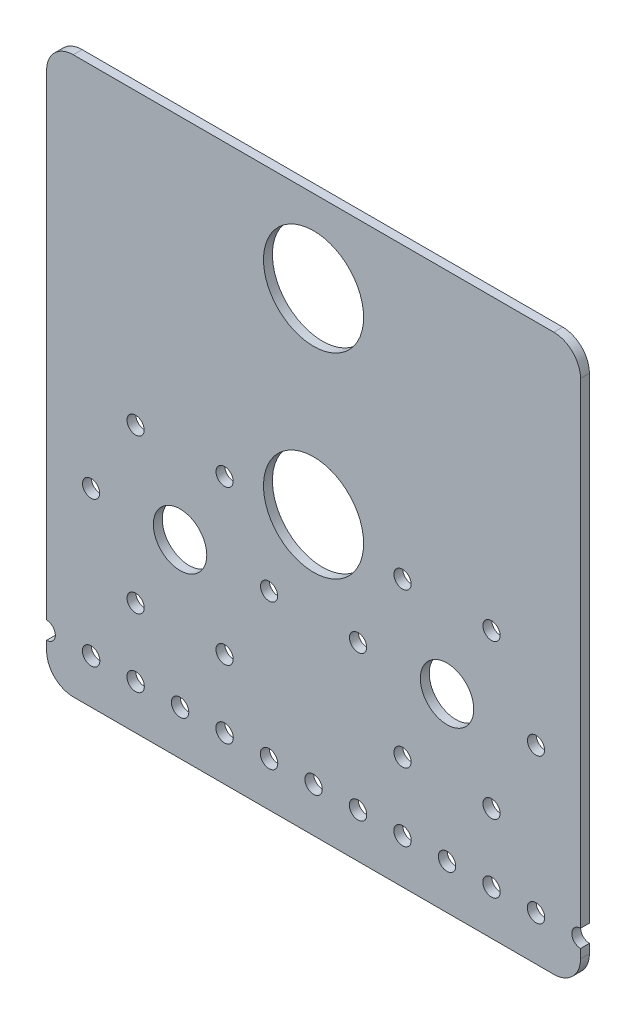
SolidWorks part; units mm, degrees
ref_plane "Front Plane" through (0, 0, 0) normal (0, 0, 1) x (1, 0, 0)
ref_plane "Top Plane" through (0, 0, 0) normal (0, 1, 0) x (1, 0, 0)
ref_plane "Right Plane" through (0, 0, 0) normal (1, 0, 0) x (0, 0, -1)
sketch "Sketch1" plane through (0, 0, 0) normal (0, 0, 1) x (1, 0, 0)
  line L0 (38.1, 28.7023) -> (25.4, 50.6994) construction
  line L1 (-38.1, 28.7023) -> (-50.8, 50.6994) construction
  line L2 (-95.25, -25.4) -> (-95.25, 0)
  line L3 (-95.25, 0) -> (-95.25, 107.95)
  line L6 (95.25, 107.95) -> (95.25, -25.4)
  line L7 (95.25, -25.4) -> (-95.25, -25.4)
  line L8 (-69.85, 133.35) -> (69.85, 133.35)
  line L10 (-95.25, 0) -> (95.25, 0) construction
  line L11 (-76.2, 133.35) -> (76.2, 133.35)
  line L12 (101.6, -12.7) -> (88.9, -12.7) construction
  line L13 (-95.25, 107.95) -> (-95.25, 133.35)
  line L14 (-95.25, 133.35) -> (-69.85, 133.35)
  line L15 (0, 53.975) -> (0, 133.35) construction
  line L16 (95.25, 107.95) -> (95.25, 133.35)
  line L17 (95.25, 133.35) -> (69.85, 133.35)
  line L18 (0, 0) -> (0, -25.4) construction
  line L19 (-76.2, 133.35) -> (-76.2, -25.4)
  line L20 (-76.2, -25.4) -> (76.2, -25.4)
  line L21 (76.2, 133.35) -> (76.2, -25.4)
  line L22 (0, 53.975) -> (0, 109.855)
  circle A0 centre (38.1, 28.7023) radius 7.62
  circle A1 centre (-38.1, 28.7023) radius 7.62
  circle A2 centre (0, 53.975) radius 38.1
  circle A3 centre (0, 53.975) radius 10.16
  circle A5 centre (-38.1, 28.7023) radius 25.4 construction
  circle A6 centre (38.1, 28.7023) radius 25.4 construction
  circle A7 centre (-50.8, 50.6994) radius 2.4511
  circle A8 centre (25.4, 50.6994) radius 2.4511
  circle A9 centre (50.8, 50.6994) radius 2.4511
  circle A10 centre (63.5, 28.7023) radius 2.4511
  circle A11 centre (50.8, 6.7053) radius 2.4511
  circle A12 centre (25.4, 6.7053) radius 2.4511
  circle A13 centre (12.7, 28.7023) radius 2.4511
  circle A14 centre (-25.4, 50.6994) radius 2.4511
  circle A15 centre (-12.7, 28.7023) radius 2.4511
  circle A16 centre (-25.4, 6.7053) radius 2.4511
  circle A17 centre (-50.8, 6.7053) radius 2.4511
  circle A18 centre (-63.5, 28.7023) radius 2.4511
  circle A19 centre (-38.1, 28.7023) radius 9.525
  circle A20 centre (38.1, 28.7023) radius 9.525
  circle A21 centre (0, 53.975) radius 14.2875
  circle A23 centre (101.6, -12.7) radius 2.4892
  circle A24 centre (88.9, -12.7) radius 2.4892
  circle A25 centre (76.2, -12.7) radius 2.4892
  circle A26 centre (63.5, -12.7) radius 2.4892
  circle A27 centre (50.8, -12.7) radius 2.4892
  circle A28 centre (38.1, -12.7) radius 2.4892
  circle A29 centre (25.4, -12.7) radius 2.4892
  circle A30 centre (12.7, -12.7) radius 2.4892
  circle A31 centre (0, -12.7) radius 2.4892
  circle A32 centre (-12.7, -12.7) radius 2.4892
  circle A33 centre (-25.4, -12.7) radius 2.4892
  circle A34 centre (-38.1, -12.7) radius 2.4892
  circle A35 centre (-50.8, -12.7) radius 2.4892
  circle A36 centre (-63.5, -12.7) radius 2.4892
  circle A37 centre (-76.2, -12.7) radius 2.4892
  circle A38 centre (-88.9, -12.7) radius 2.4892
  circle A39 centre (0, 109.855) radius 14.2875
  point P89 (0, 0)
  point P90 (0, 0)
  point P91 (102.1917, -12.7)
  point P92 (0, 0)
  point P93 (0, 0)
  point P95 (0, 0)
  point P96 (0, 0)
  dimension "D1" = 15.24
  dimension "D2" = 76.2
  dimension "D5" = 20.32
  dimension "D6" = 6.35
  dimension "D7" = 50.8
  dimension "D8" = 4.9022
  dimension "D14" = 19.05
  dimension "D15" = 28.575
  dimension "D25" = 4.9784
  dimension "D17" = 28.575
  dimension "D3" = 25.4
  dimension "D4" = 79.375
  dimension "D10" = 76.2
  dimension "D16" = 55.88
  dimension "D19" = 25.4
  dimension "D21" = 139.7
  dimension "D22" = 158.75
  dimension "D23" = 25.4
  dimension "D26" = 12.7
  dimension "D28" = 12.7
  dimension "D27" = 16
  dimension "D9" = 6
  dimension "D11" = 6
extrude "Boss-Extrude1" add sketch "Sketch1" along normal blind 2.54
fillet "Fillet1" radius 7.62 4 edges at (76.2, -25.4, 1.27) (-76.2, -25.4, 1.27) (76.2, 133.35, 1.27) (-76.2, 133.35, 1.27)
